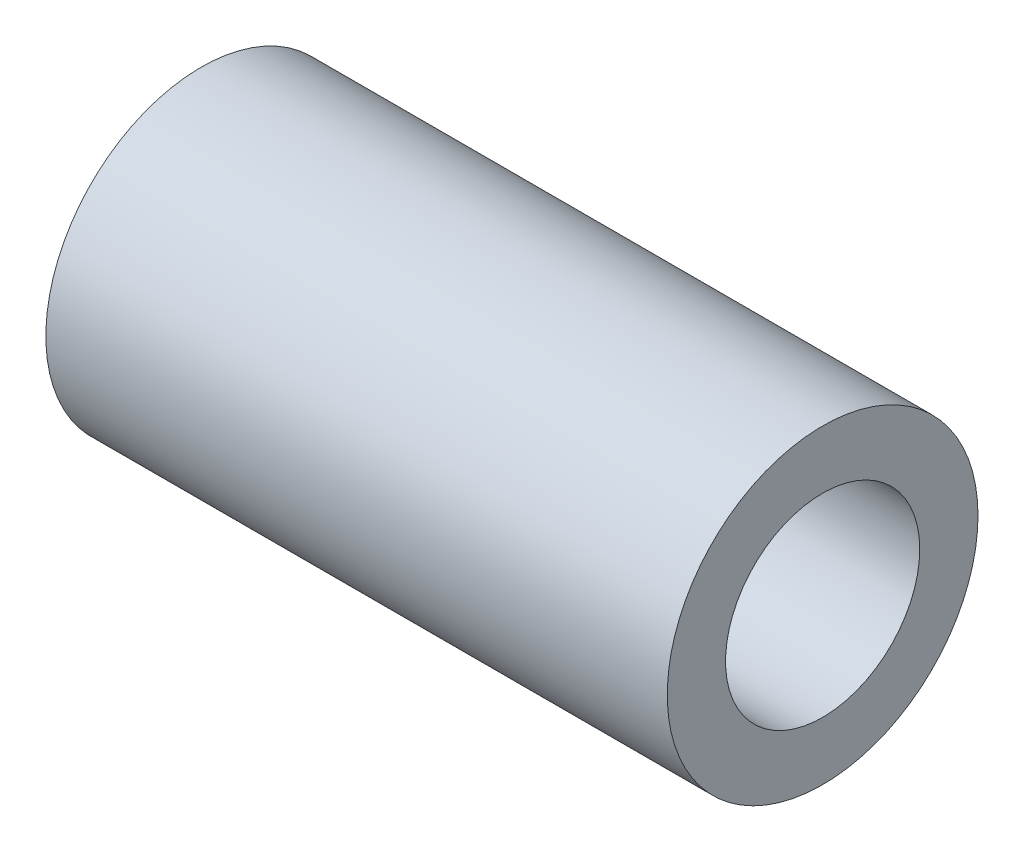
SolidWorks part; units mm, degrees
material "2.1016 (CuSn4)"
ref_plane "前视基准面" through (0, 0, 0) normal (0, 0, 1) x (1, 0, 0)
ref_plane "上视基准面" through (0, 0, 0) normal (0, 1, 0) x (1, 0, 0)
ref_plane "右视基准面" through (0, 0, 0) normal (1, 0, 0) x (0, 0, -1)
other "Configuration Table"
sketch "草图1" plane through (0, 0, 0) normal (1, 0, 0) x (0, 0, -1)
  circle A0 centre (0, 0) radius 2
  circle A1 centre (0, 0) radius 1.25
  dimension "D1" = 4
  dimension "D2" = 2.5
extrude "凸台-拉伸1" add sketch "草图1" along normal blind 8
